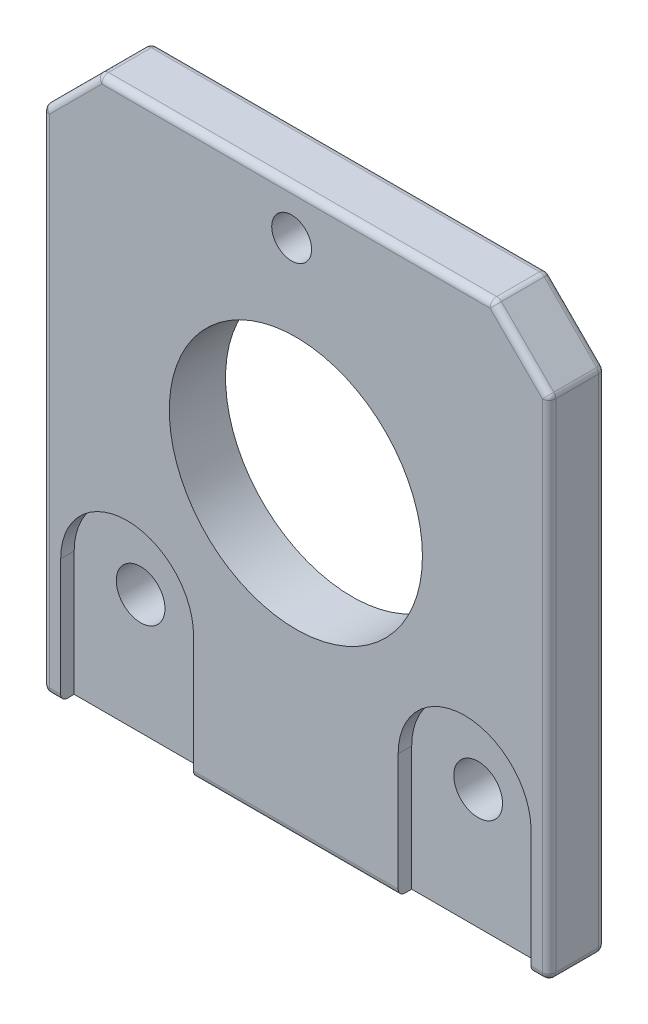
SolidWorks part; units mm, degrees
ref_plane "Front Plane" through (0, 0, 0) normal (0, 0, 1) x (1, 0, 0)
ref_plane "Top Plane" through (0, 0, 0) normal (0, 1, 0) x (1, 0, 0)
ref_plane "Right Plane" through (0, 0, 0) normal (1, 0, 0) x (0, 0, -1)
sketch "Sketch2" plane through (0, 0, 0) normal (0, 1, 0) x (1, 0, 0)
  line L1 (-28.575, 3.175) -> (28.575, 3.175)
  line L2 (-28.575, 3.175) -> (-28.575, -3.175)
  line L3 (-28.575, -3.175) -> (28.575, -3.175)
  line L4 (28.575, 3.175) -> (28.575, -3.175)
  point P4 (0, 3.175)
  point P7 (-28.575, 0)
  dimension "D1" = 6.35
  dimension "D2" = 57.15
extrude "Boss-Extrude1" add sketch "Sketch2" against normal blind 63.5
sketch "Sketch3" plane through (0, 0, 3.175) normal (0, 0, 1) x (1, 0, 0)
  line L2 (-28.575, 0) -> (28.575, 0) construction
  circle A0 centre (0, -28.815) radius 14.2875
  point P2 (0, 0)
  dimension "D1" = 28.815
  dimension "D3" = 28.575
extrude "Cut-Extrude1" cut sketch "Sketch3" against normal through all
chamfer "Chamfer1" distance 6.35 angle 45 2 edges at (-28.575, 0, 0) (28.575, 0, 0)
hole_wizard "M4 Clearance Hole1" positions "Sketch4" profile "Sketch5" hole size "M4" standard "ANSI Metric" end condition through all
sketch "Sketch4" plane through (0, 0, -3.175) normal (0, 0, -1) x (-1, 0, 0)
  point P0 (0.4796, -5.0844)
sketch "Sketch5" plane through (-0.4796, -5.0844, -3.175) normal (1, 0, 0) x (0, 1, 0)
  line L0 (0, 0) -> (0, 6.35)
  line L1 (0, 6.35) -> (2.25, 6.35)
  line L2 (2.25, 6.35) -> (2.25, 0)
  line L5 (2.25, 0) -> (0, 0)
  line L11 (0, -6.35) -> (0, 107.95) construction
  dimension "Thru Hole Dia." = 4.5
  dimension "Thru Hole Depth" = 6.35
hole_wizard "M5 Clearance Hole1" positions "Sketch6" profile "Sketch7" hole size "M5" standard "ANSI Metric" end condition through all
sketch "Sketch6" plane through (0, 0, 3.175) normal (0, 0, 1) x (1, 0, 0)
  line L0 (-28.575, -63.5) -> (28.575, -63.5) construction
  line L1 (28.575, -63.5) -> (28.575, -6.35) construction
  point P0 (-19.05, -50)
  point P3 (19.05, -50)
  dimension "D1" = 13.5
  dimension "D2" = 9.525
  dimension "D3" = 38.1
sketch "Sketch7" plane through (-19.05, -50, 3.175) normal (1, 0, 0) x (0, -1, 0)
  line L0 (0, 0) -> (0, 6.35)
  line L1 (0, 6.35) -> (2.75, 6.35)
  line L2 (2.75, 6.35) -> (2.75, 0)
  line L5 (2.75, 0) -> (0, 0)
  line L11 (0, -6.35) -> (0, 107.95) construction
  dimension "Thru Hole Dia." = 5.5
  dimension "Thru Hole Depth" = 6.35
fillet "Fillet1" radius 0.762 18 edges at (0, -63.5, 3.175) (0, -63.5, -3.175) (28.575, -63.5, 0) (28.575, -34.925, 3.175) (28.575, -34.925, -3.175) (-28.575, -63.5, 0) (-28.575, -34.925, -3.175) (-28.575, -34.925, 3.175) (-25.4, -3.175, 3.175) (-28.575, -6.35, 0) (-25.4, -3.175, -3.175) (0, 0, 3.175) (-22.225, 0, 0) (0, 0, -3.175) (22.225, 0, 0) (25.4, -3.175, -3.175) (28.575, -6.35, 0) (25.4, -3.175, 3.175)
sketch "Sketch8" plane through (0, 0, 3.175) normal (0, 0, 1) x (1, 0, 0)
  line L0 (11.55, -63.5) -> (11.55, -49.5)
  line L1 (26.55, -49.5) -> (26.55, -63.5)
  line L2 (11.55, -63.5) -> (26.55, -63.5)
  arc A0 (11.55, -49.5) -> (26.55, -49.5) centre (19.05, -49.5) cw
extrude "Cut-Extrude4" cut sketch "Sketch8" against normal blind 1.524
mirror "Mirror1" about plane through (0, 0, 0) normal (1, 0, 0) of "Cut-Extrude4"
